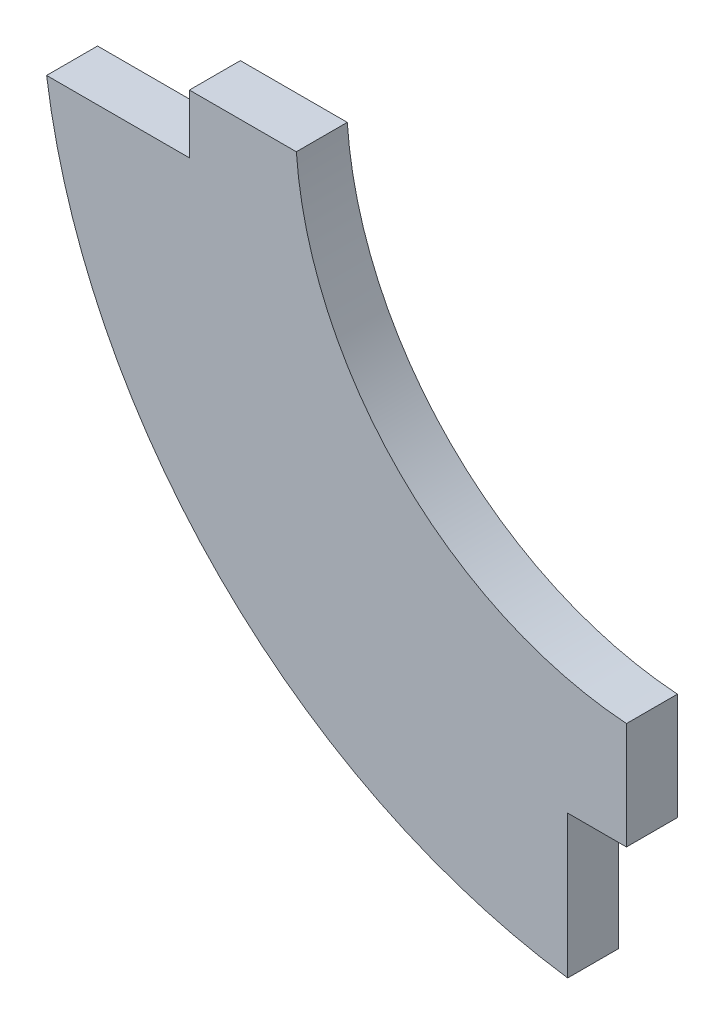
SolidWorks part; units mm, degrees
material "mdf"
ref_plane "Front Plane" through (0, 0, 0) normal (0, 0, 1) x (1, 0, 0)
ref_plane "Top Plane" through (0, 0, 0) normal (0, 1, 0) x (1, 0, 0)
ref_plane "Right Plane" through (0, 0, 0) normal (1, 0, 0) x (0, 0, -1)
sketch "Sketch1" plane through (0, 0, 0) normal (0, 0, 1) x (1, 0, 0)
  line L0 (-6.35, -88.6729) -> (-6.35, -115.332)
  line L1 (-6.35, 250) -> (-6.35, -250) construction
  line L2 (-6.35, -115.332) -> (-21, -115.332)
  line L3 (-21, -115.332) -> (-21, -150.9462)
  line L5 (-88.6729, -6.35) -> (-115.332, -6.35)
  line L7 (-115.332, -6.35) -> (-115.332, -21)
  line L8 (-115.332, -21) -> (-150.9462, -21)
  arc A0 (-150.9462, -21) -> (-21, -150.9462) centre (0, 0) ccw
  arc A1 (-88.6729, -6.35) -> (-6.35, -88.6729) centre (0, 0) ccw
  dimension "D1" = 304.8
  dimension "D2" = 177.8
  dimension "D3" = 35.6142
  dimension "D4" = 35.6142
extrude "Boss-Extrude1" add sketch "Sketch1" along normal mid plane 12.7 contours A0 L3 L2 L0 A1 L5 L7 L8
